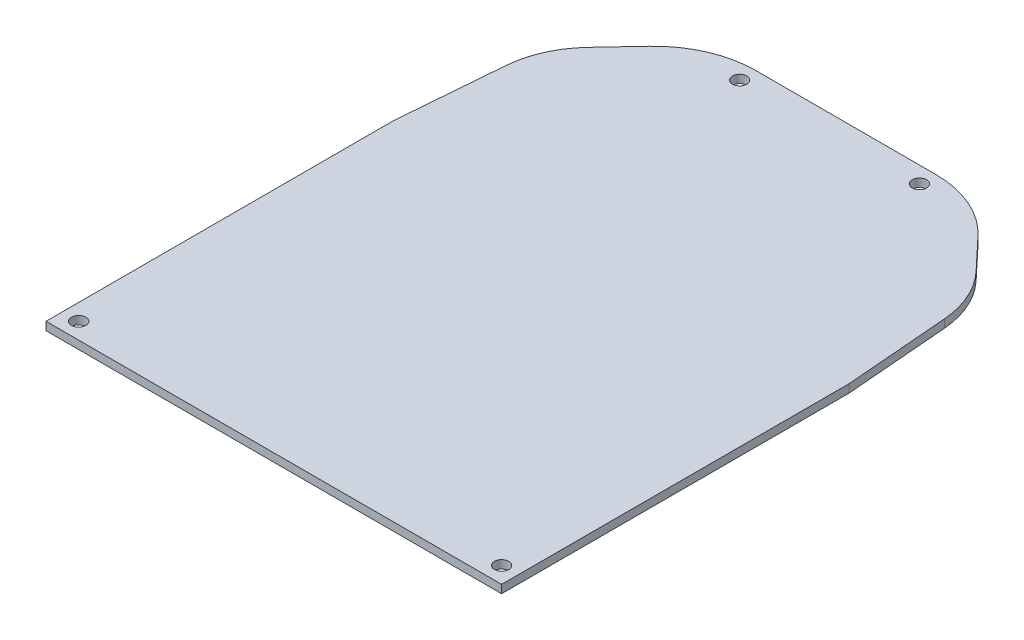
SolidWorks part; units mm, degrees
ref_plane "Plan de face" through (0, 0, 0) normal (0, 0, 1) x (1, 0, 0)
ref_plane "Plan de dessus" through (0, 0, 0) normal (0, 1, 0) x (1, 0, 0)
ref_plane "Plan de droite" through (0, 0, 0) normal (1, 0, 0) x (0, 0, -1)
sketch "Esquisse1" plane through (0, 0, 0) normal (0, 1, 0) x (1, 0, 0)
  line L16 (-55.75, -62) -> (-55.75, -70)
  line L17 (-55.75, -70) -> (55.75, -70)
  line L18 (55.75, -70) -> (55.75, -62)
  line L19 (55.75, -62) -> (-55.75, -62)
  line L26 (55.75, -62) -> (55.75, 15)
  line L27 (55.75, 15) -> (53.674, 40.4778)
  line L28 (47.5102, 54.3609) -> (40.2176, 62.1207)
  line L29 (22, 70) -> (-22, 70)
  line L30 (-40.2176, 62.1207) -> (-47.5102, 54.3609)
  line L31 (-53.674, 40.4778) -> (-55.75, 15)
  line L32 (-55.75, 15) -> (-55.75, -62)
  line L36 (-55.75, -70) -> (-55.75, 70)
  line L37 (-55.75, 70) -> (55.75, 70)
  line L38 (55.75, 70) -> (55.75, -70)
  line L39 (-55.75, 70) -> (55.75, -70) construction
  line L40 (55.75, 70) -> (-55.75, -70) construction
  line L50 (-22, 66) -> (22, 66) construction
  line L51 (-55.75, -66) -> (-51.75, -66) construction
  line L53 (-51.75, -66) -> (-51.75, -70) construction
  line L54 (51.75, -66) -> (55.75, -66) construction
  line L55 (51.75, -66) -> (51.75, -70) construction
  arc A0 (53.674, 40.4778) -> (47.5102, 54.3609) centre (30.75, 38.6099) ccw
  arc A1 (40.2176, 62.1207) -> (22, 70) centre (22, 45) ccw
  arc A2 (-22, 70) -> (-40.2176, 62.1207) centre (-22, 45) ccw
  arc A3 (-47.5102, 54.3609) -> (-53.674, 40.4778) centre (-30.75, 38.6099) ccw
  circle A8 centre (51.75, -66) radius 1.75
  circle A9 centre (-51.75, -66) radius 1.75
  circle A10 centre (-22, 66) radius 1.75
  circle A11 centre (22, 66) radius 1.75
  point P5 (0, 0)
  dimension "D5" = 3.5
  dimension "D1" = 23
  dimension "D6" = 25
  dimension "D2" = 111.5
  dimension "D3" = 140
  dimension "D4" = 8
  dimension "D7" = 22
  dimension "D8" = 30.75
  dimension "D9" = 40.2176
  dimension "D10" = 53.674
  dimension "D11" = 4
extrude "Boss.-Extru.1" add sketch "Esquisse1" along normal blind 2
